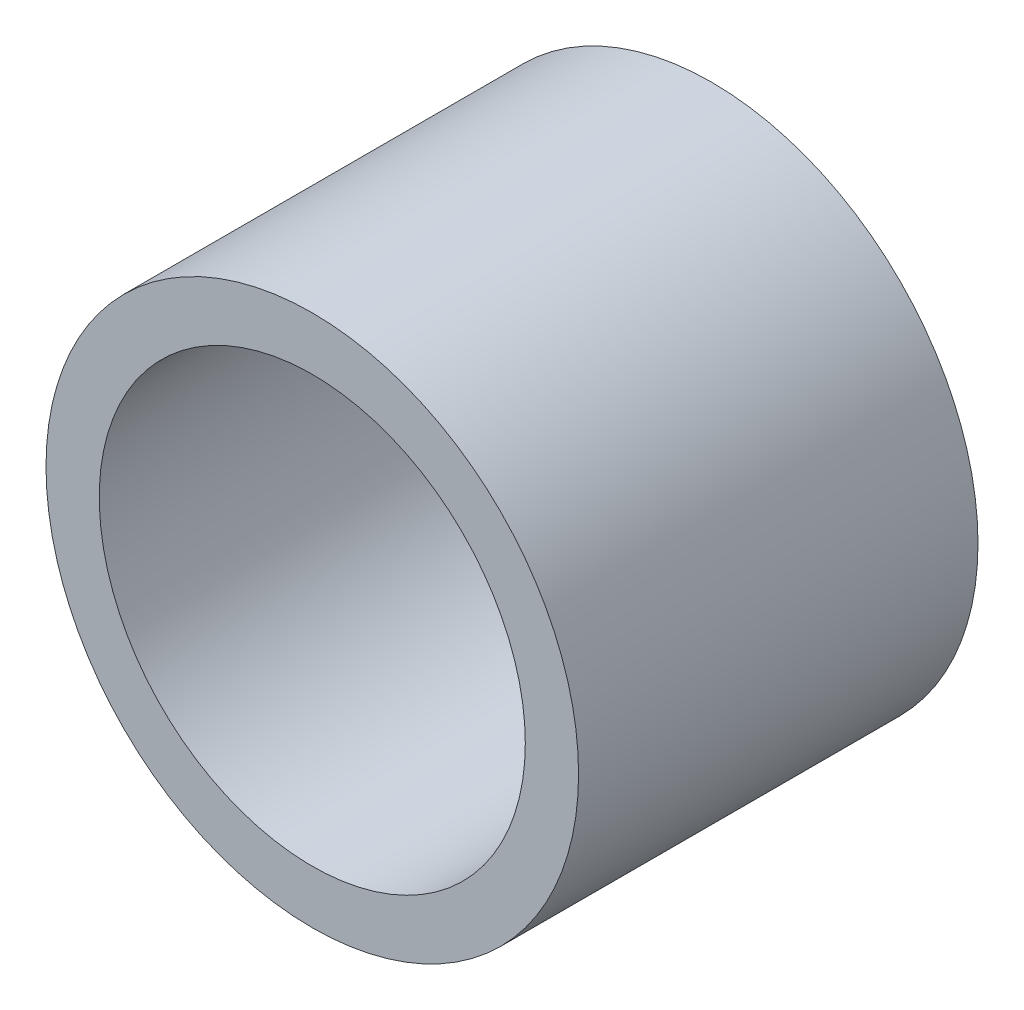
SolidWorks part; units mm, degrees
ref_plane "Front Plane" through (0, 0, 0) normal (0, 0, 1) x (1, 0, 0)
ref_plane "Top Plane" through (0, 0, 0) normal (0, 1, 0) x (1, 0, 0)
ref_plane "Right Plane" through (0, 0, 0) normal (1, 0, 0) x (0, 0, -1)
sketch "Sketch1" plane through (0, 0, 0) normal (0, 0, 1) x (1, 0, 0)
  circle A0 centre (213.8034, -339.8662) radius 5
  circle A1 centre (213.8034, -339.8662) radius 4
  dimension "D1" = 8
  dimension "D2" = 10
extrude "Boss-Extrude1" add sketch "Sketch1" along normal blind 7.5
